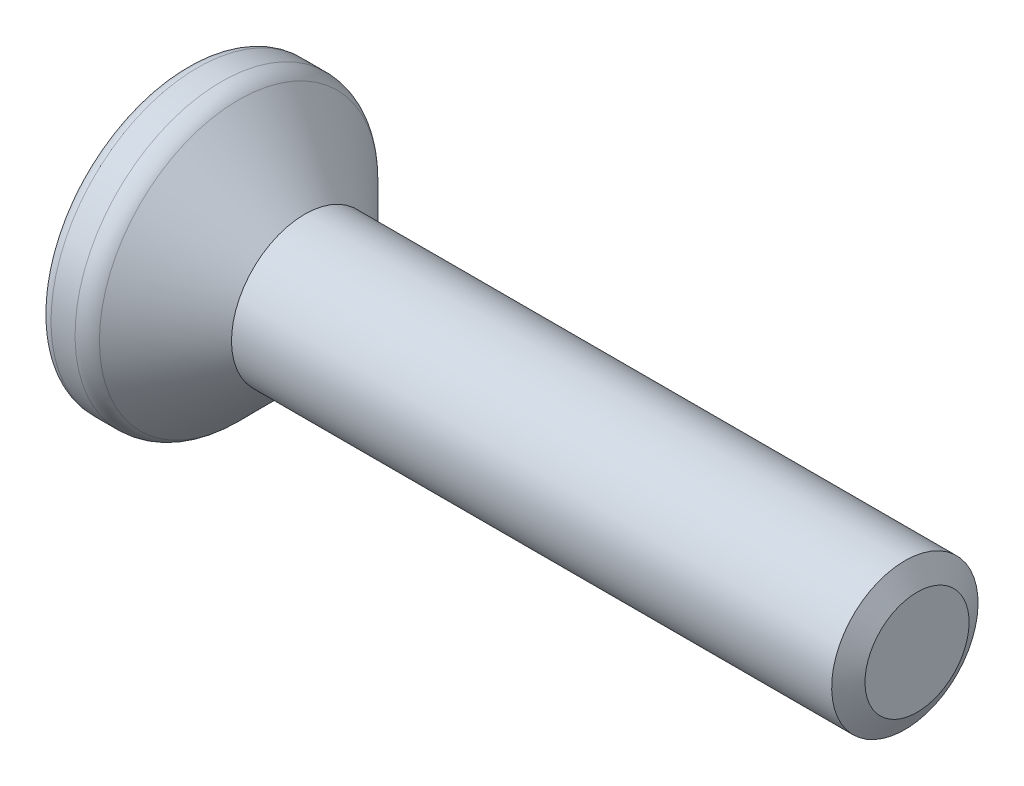
SolidWorks part; units mm, degrees
ref_plane "前视基准面" through (0, 0, 0) normal (0, 0, 1) x (1, 0, 0)
ref_plane "上视基准面" through (0, 0, 0) normal (0, 1, 0) x (1, 0, 0)
ref_plane "右视基准面" through (0, 0, 0) normal (1, 0, 0) x (0, 0, -1)
sketch "草图1" plane through (0, 0, 0) normal (0, 0, 1) x (1, 0, 0)
  line L0 (15, 0) -> (-15, 0)
  line L1 (-15, 0) -> (-15, 6)
  line L2 (-15, 6) -> (-13.1, 6)
  line L3 (-13.1, 6) -> (-10.1, 3)
  line L4 (-10.1, 3) -> (15, 3)
  line L5 (15, 3) -> (15, 0)
  point P5 (0, 0)
  dimension "D1" = 4.9
  dimension "D2" = 6
  dimension "D3" = 3
  dimension "D4" = 45
  dimension "D5" = 30
revolve "旋转1" add sketch "草图1" angle 360 about L0
fillet "圆角1" radius 0.5 1 edges at (-15, 6, 0)
fillet "圆角2" radius 1 1 edges at (-13.1, 6, 0)
sketch "草图2" plane through (-15, 0, 0) normal (-1, 0, 0) x (0, 0, 1)
  line L1 (0, 2.3094) -> (-2, 1.1547)
  line L2 (-2, 1.1547) -> (-2, -1.1547)
  line L3 (-2, -1.1547) -> (0, -2.3094)
  line L4 (0, -2.3094) -> (2, -1.1547)
  line L5 (2, -1.1547) -> (2, 1.1547)
  line L6 (2, 1.1547) -> (0, 2.3094)
  circle A0 centre (0, 0) radius 2 construction
  dimension "D1" = 4
extrude "切除-拉伸1" cut sketch "草图2" against normal blind 2.5
chamfer "倒角1" distance 0.5 angle 60 1 edges at (15, 3, 0)
